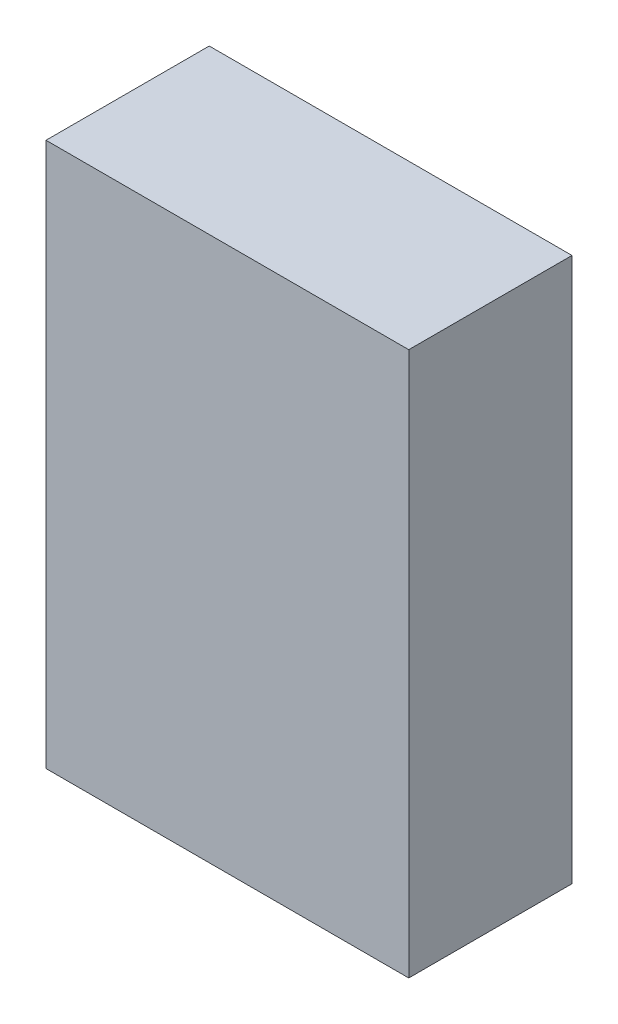
SolidWorks part; units mm, degrees
ref_plane "Front Plane" through (0, 0, 0) normal (0, 0, 1) x (1, 0, 0)
ref_plane "Top Plane" through (0, 0, 0) normal (0, 1, 0) x (1, 0, 0)
ref_plane "Right Plane" through (0, 0, 0) normal (1, 0, 0) x (0, 0, -1)
sketch "Sketch1" plane through (0, 0, 0) normal (0, 0, 1) x (1, 0, 0)
  line L1 (-63.5, 95.25) -> (63.5, 95.25)
  line L2 (-63.5, 95.25) -> (-63.5, -95.25)
  line L3 (-63.5, -95.25) -> (63.5, -95.25)
  line L4 (63.5, 95.25) -> (63.5, -95.25)
  line L5 (-63.5, 95.25) -> (63.5, -95.25) construction
  line L6 (-63.5, -95.25) -> (63.5, 95.25) construction
  point P0 (0, 0)
  dimension "D1" = 127
  dimension "D2" = 190.5
extrude "Boss-Extrude1" add sketch "Sketch1" along normal blind 57.15
